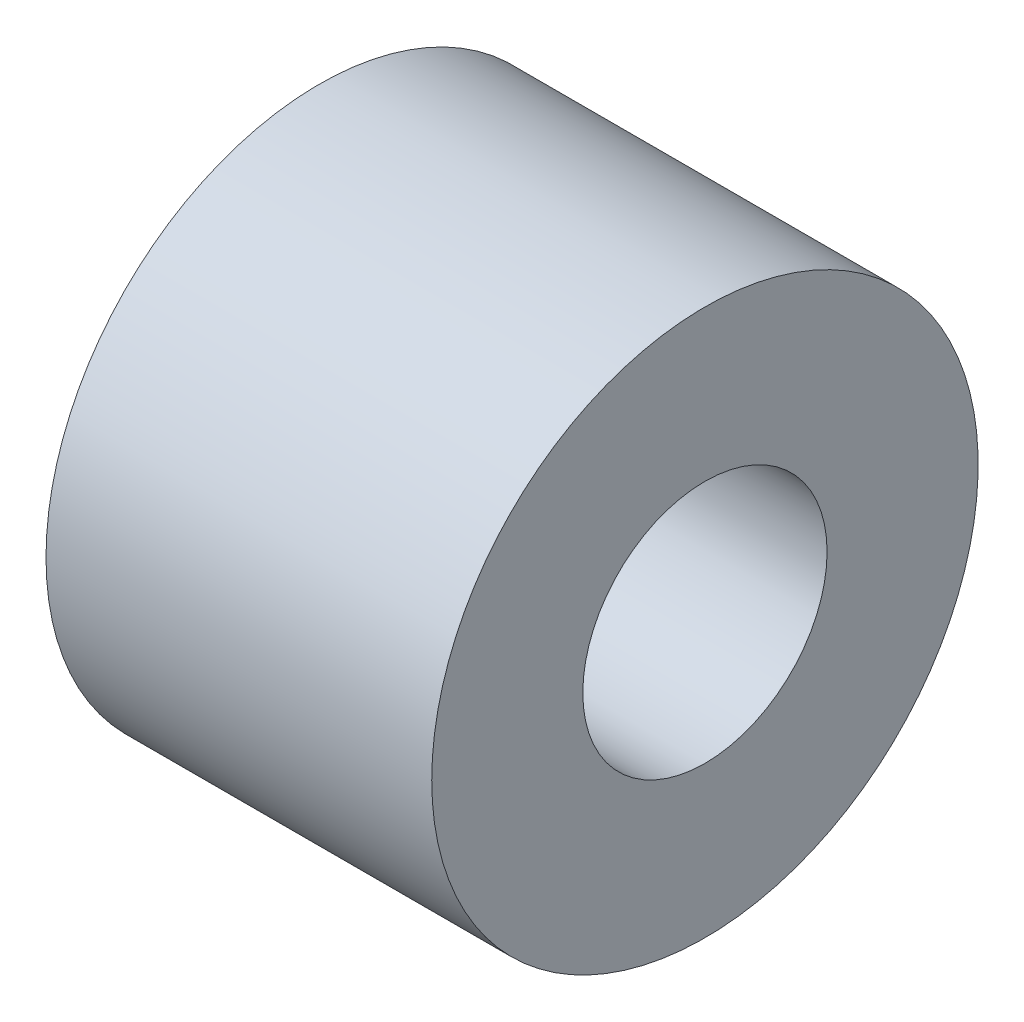
SolidWorks part; units mm, degrees
material "6061 Alloy"
ref_plane "Front" through (0, 0, 0) normal (0, 0, 1) x (1, 0, 0)
ref_plane "Top" through (0, 0, 0) normal (0, 1, 0) x (1, 0, 0)
ref_plane "Right" through (0, 0, 0) normal (1, 0, 0) x (0, 0, -1)
sketch "Sketch1" plane through (0, 0, 0) normal (1, 0, 0) x (0, 0, -1)
  circle A0 centre (0, 0) radius 5.3975
  circle A1 centre (0, 0) radius 2.413
  dimension "D1" = 4.826
  dimension "D2" = 10.795
extrude "Boss-Extrude1" add sketch "Sketch1" along normal mid plane 7.62
